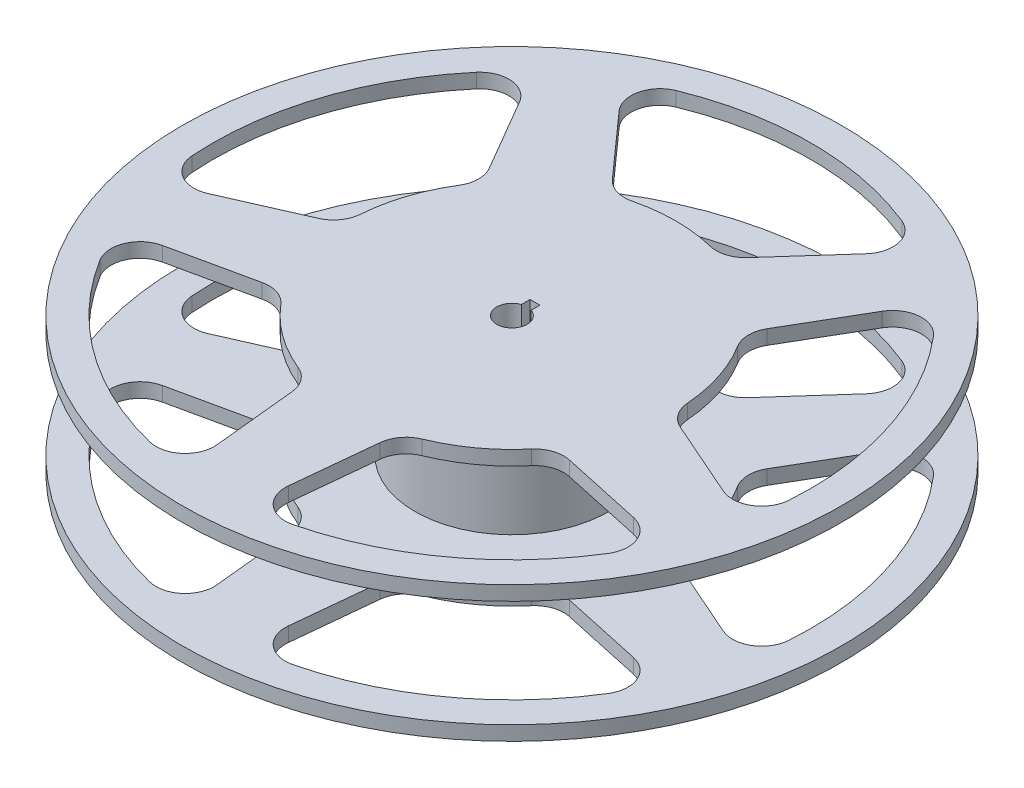
SolidWorks part; units mm, degrees
material "1023 Carbon Steel Sheet (SS)"
ref_plane "Front Plane" through (0, 0, 0) normal (0, 0, 1) x (1, 0, 0)
ref_plane "Top Plane" through (0, 0, 0) normal (0, 1, 0) x (1, 0, 0)
ref_plane "Right Plane" through (0, 0, 0) normal (1, 0, 0) x (0, 0, -1)
sketch "Sketch1" plane through (0, 0, 0) normal (0, 0, 1) x (1, 0, 0)
  line L0 (0, 0) -> (86.36, 0)
  line L1 (86.36, 0) -> (86.36, 3.78)
  line L2 (86.36, 3.78) -> (25.4, 3.78)
  line L3 (25.4, 3.78) -> (25.4, 31.78)
  line L4 (25.4, 31.78) -> (86.36, 31.78)
  line L5 (86.36, 31.78) -> (86.36, 35.56)
  line L6 (86.36, 35.56) -> (0, 35.56)
  line L7 (0, 35.56) -> (0, 0)
  dimension "D1" = 35.56
  dimension "D2" = 86.36
  dimension "D3" = 28
  dimension "D4" = 25.4
revolve "Revolve1" add sketch "Sketch1" angle 360 about L7
sketch "Sketch2" plane through (0, 35.56, 0) normal (0, 1, 0) x (1, 0, 0)
  line L0 (0, 0) -> (0, 86.36) construction
  line L1 (-32.3832, 60.4614) -> (-17.7368, 44.056)
  line L2 (32.3832, 60.4614) -> (17.7368, 44.056)
  circle A0 centre (0, 0) radius 86.36 construction
  arc A1 (-29.5739, 72.5931) -> (29.5739, 72.5931) centre (0, 0) cw
  arc A2 (-10.2371, 41.7302) -> (10.2371, 41.7302) centre (0, 0) cw
  arc A3 (-29.5739, 72.5931) -> (-32.3832, 60.4614) centre (-26.699, 65.5362) ccw
  arc A4 (-10.2371, 41.7302) -> (-17.7368, 44.056) centre (-12.0525, 49.1308) cw
  arc A5 (10.2371, 41.7302) -> (17.7368, 44.056) centre (12.0525, 49.1308) ccw
  arc A6 (29.5739, 72.5931) -> (32.3832, 60.4614) centre (26.699, 65.5362) cw
  dimension "D1" = 7.62
  dimension "D2" = 7.62
extrude "Cut-Extrude1" cut sketch "Sketch2" against normal through all
pattern_circular "CirPattern1" count 5 over 360 about axis through (0, 0, 0) along (0, 1, 0) of "Cut-Extrude1"
sketch "Sketch3" plane through (0, 35.56, 0) normal (0, 1, 0) x (1, 0, 0)
  line L0 (-1.2892, 3.7535) -> (-1.2892, 6.0494)
  line L1 (-1.2892, 6.0494) -> (1.2892, 6.0494)
  line L2 (1.2892, 6.0494) -> (1.2892, 3.7535)
  line L3 (0, 0) -> (0, 6.0494) construction
  arc A0 (-1.2892, 3.7535) -> (1.2892, 3.7535) centre (0, 0) ccw
  dimension "D1" = 7.9375
extrude "Cut-Extrude2" cut sketch "Sketch3" against normal through all
